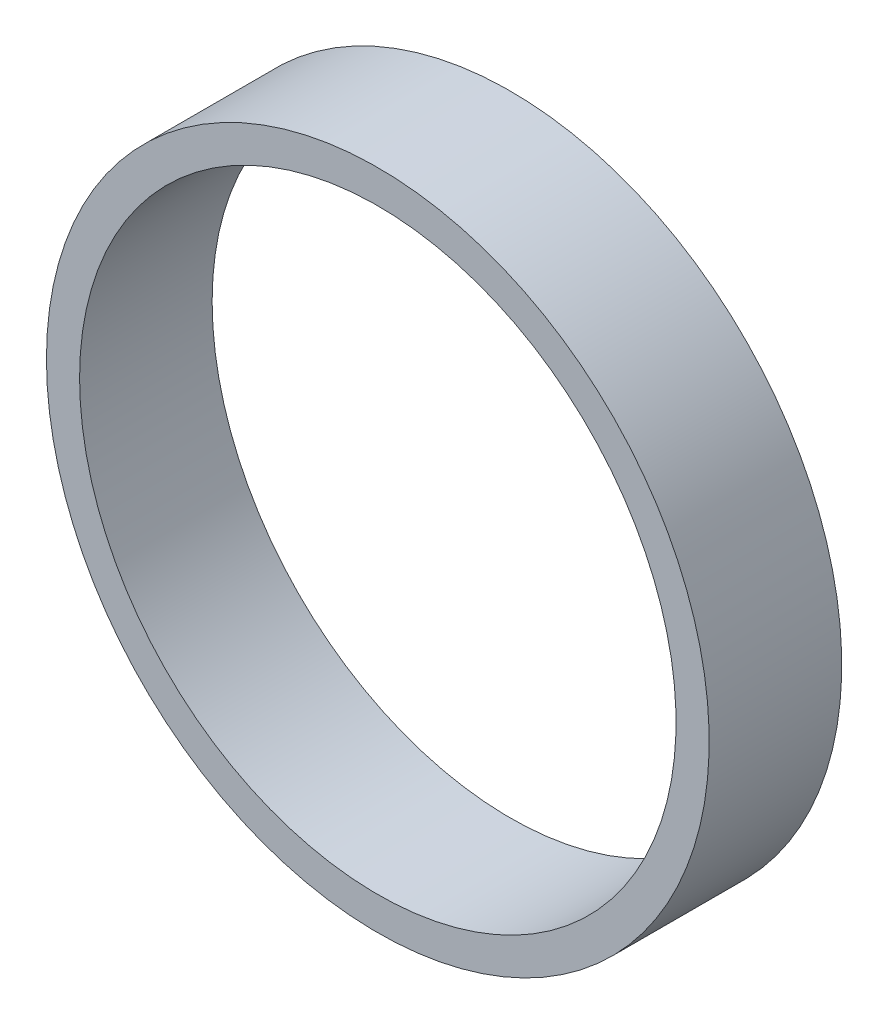
SolidWorks part; units mm, degrees
ref_plane "Front Plane" through (0, 0, 0) normal (0, 0, 1) x (1, 0, 0)
ref_plane "Top Plane" through (0, 0, 0) normal (0, 1, 0) x (1, 0, 0)
ref_plane "Right Plane" through (0, 0, 0) normal (1, 0, 0) x (0, 0, -1)
sketch "Sketch1" plane through (0, 0, 0) normal (0, 1, 0) x (1, 0, 0)
  line L0 (-149.784, 0) -> (168.4058, 0) construction
  line L1 (0, 132.3767) -> (0, -165.5721) construction
  line L2 (-45, 10) -> (-45, -10)
  line L3 (-50, 10) -> (-45, 10)
  line L4 (-50, 10) -> (-50, -10)
  line L5 (-50, -10) -> (-45, -10)
  point P5 (0, 0)
  dimension "D1" = 45
  dimension "D2" = 5
  dimension "D3" = 20
revolve "Revolve2" add sketch "Sketch1" angle 360 about L1
